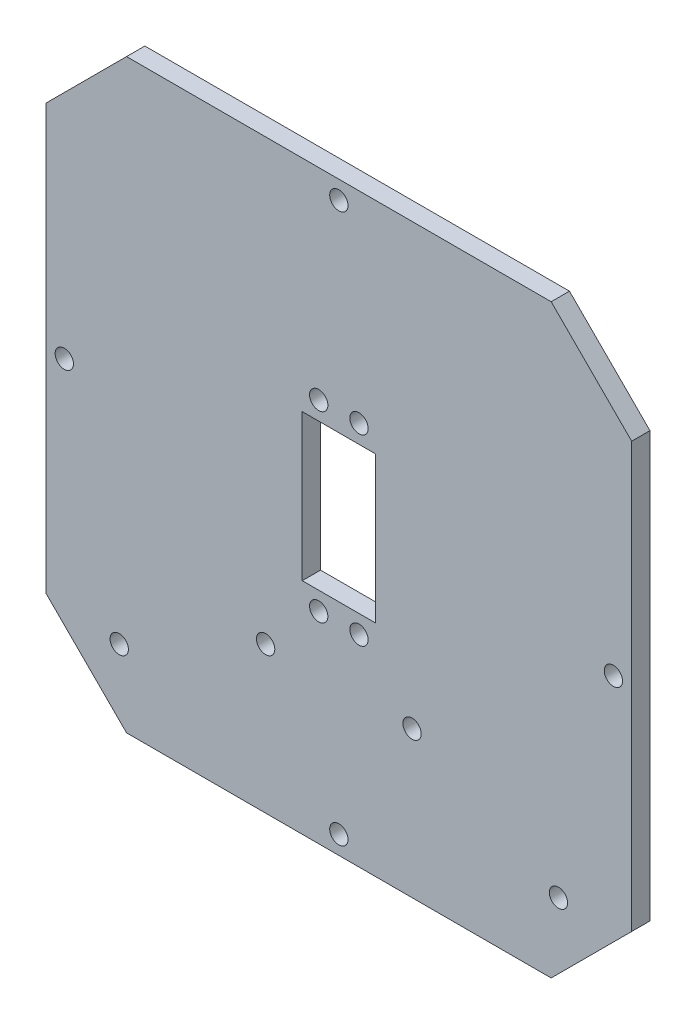
SolidWorks part; units mm, degrees
ref_plane "Plan de face" through (0, 0, 0) normal (0, 0, 1) x (1, 0, 0)
ref_plane "Plan de dessus" through (0, 0, 0) normal (0, 1, 0) x (1, 0, 0)
ref_plane "Plan de droite" through (0, 0, 0) normal (1, 0, 0) x (0, 0, -1)
sketch "Esquisse1" plane through (0, 0, 0) normal (0, 0, 1) x (1, 0, 0)
  line L1 (-28.3501, 34.1568) -> (131.6499, 34.1568)
  line L2 (-28.3501, 34.1568) -> (-28.3501, -125.8432)
  line L3 (-28.3501, -125.8432) -> (131.6499, -125.8432)
  line L4 (131.6499, 34.1568) -> (131.6499, -125.8432)
  dimension "D1" = 160
  dimension "D2" = 160
extrude "Boss.-Extru.1" add sketch "Esquisse1" along normal blind 5
chamfer "Chanfrein1" distance 22 angle 45 4 edges at (-28.3501, -125.8432, 2.5) (131.6499, -125.8432, 2.5) (131.6499, 34.1568, 2.5) (-28.3501, 34.1568, 2.5)
sketch "Esquisse2" plane through (0, 0, 5) normal (0, 0, 1) x (1, 0, 0)
  line L0 (131.6499, -103.8432) -> (131.6499, 12.1568) construction
  line L1 (41.6499, -25.8432) -> (61.6499, -25.8432)
  line L2 (41.6499, -25.8432) -> (41.6499, -65.8432)
  line L3 (41.6499, -65.8432) -> (61.6499, -65.8432)
  line L4 (61.6499, -25.8432) -> (61.6499, -65.8432)
  line L5 (109.6499, 34.1568) -> (-6.3501, 34.1568) construction
  dimension "D1" = 20
  dimension "D2" = 40
  dimension "D3" = 70
  dimension "D4" = 60
extrude "Enlèv. mat.-Extru.1" cut sketch "Esquisse2" against normal blind 5
sketch "Esquisse3" plane through (0, 0, 5) normal (0, 0, 1) x (1, 0, 0)
  line L0 (61.6499, -25.8432) -> (41.6499, -25.8432) construction
  line L1 (41.6499, -25.8432) -> (41.6499, -65.8432) construction
  line L2 (61.6499, -65.8432) -> (61.6499, -25.8432) construction
  line L3 (61.6499, -25.8432) -> (41.6499, -25.8432) construction
  circle A0 centre (46.1499, -20.8432) radius 2.5
  circle A1 centre (57.1499, -20.8432) radius 2.5
  dimension "D2" = 5
  dimension "D4" = 5
  dimension "D1" = 5
  dimension "D3" = 4.5
  dimension "D5" = 4.5
  dimension "D6" = 5
extrude "Enlèv. mat.-Extru.2" cut sketch "Esquisse3" against normal blind 5
sketch "Esquisse4" plane through (0, 0, 5) normal (0, 0, 1) x (1, 0, 0)
  line L0 (41.6499, -25.8432) -> (41.6499, -65.8432) construction
  line L2 (41.6499, -65.8432) -> (61.6499, -65.8432) construction
  line L3 (61.6499, -65.8432) -> (61.6499, -25.8432) construction
  circle A0 centre (46.1499, -70.8432) radius 2.5
  circle A1 centre (57.1499, -61.8432) radius 2.5
  dimension "D1" = 5
  dimension "D4" = 5
  dimension "D2" = 4.5
  dimension "D3" = 5
  dimension "D5" = 4.5
extrude "Enlèv. mat.-Extru.3" cut sketch "Esquisse4" against normal blind 5
sketch "Esquisse5" plane through (0, 0, 0) normal (0, 0, -1) x (-1, 0, 0)
  line L0 (-41.6499, -65.8432) -> (-61.6499, -65.8432) construction
  line L1 (-61.6499, -65.8432) -> (-61.6499, -25.8432) construction
  circle A0 centre (-57.1499, -70.8432) radius 2.5
  dimension "D1" = 5
  dimension "D2" = 5
  dimension "D3" = 4.5
extrude "Enlèv. mat.-Extru.4" cut sketch "Esquisse5" against normal blind 10
sketch "Esquisse6" plane through (0, 0, 5) normal (0, 0, 1) x (1, 0, 0)
  line L0 (109.6499, 34.1568) -> (-6.3501, 34.1568) construction
  line L1 (-28.3501, 12.1568) -> (-28.3501, -103.8432) construction
  circle A0 centre (51.6499, 29.1568) radius 2.5
  dimension "D1" = 5
  dimension "D2" = 5
  dimension "D3" = 80
extrude "Enlèv. mat.-Extru.5" cut sketch "Esquisse6" against normal blind 10
sketch "Esquisse7" plane through (0, 0, 5) normal (0, 0, 1) x (1, 0, 0)
  line L0 (-28.3501, 12.1568) -> (-28.3501, -103.8432) construction
  line L1 (-6.3501, -125.8432) -> (109.6499, -125.8432) construction
  circle A0 centre (-23.3501, -45.8432) radius 2.5
  dimension "D2" = 5
  dimension "D1" = 5
  dimension "D3" = 80
extrude "Enlèv. mat.-Extru.6" cut sketch "Esquisse7" against normal blind 10
sketch "Esquisse8" plane through (0, 0, 5) normal (0, 0, 1) x (1, 0, 0)
  line L0 (-6.3501, -125.8432) -> (109.6499, -125.8432) construction
  line L1 (131.6499, -103.8432) -> (131.6499, 12.1568) construction
  circle A0 centre (51.6499, -120.8432) radius 2.5
  circle A1 centre (126.6499, -45.8432) radius 2.5
  dimension "D3" = 5
  dimension "D4" = 5
  dimension "D1" = 5
  dimension "D2" = 5
  dimension "D5" = 80
  dimension "D6" = 80
extrude "Enlèv. mat.-Extru.7" cut sketch "Esquisse8" against normal blind 10
sketch "Esquisse9" plane through (0, 0, 5) normal (0, 0, 1) x (1, 0, 0)
  line L0 (131.6499, -103.8432) -> (131.6499, 12.1568) construction
  line L1 (-6.3501, -125.8432) -> (109.6499, -125.8432) construction
  line L2 (-28.3501, 12.1568) -> (-28.3501, -103.8432) construction
  circle A0 centre (111.6499, -105.8432) radius 2.5
  circle A1 centre (-8.3501, -105.8432) radius 2.5
  dimension "D2" = 5
  dimension "D6" = 5
  dimension "D1" = 20
  dimension "D3" = 20
  dimension "D4" = 20
  dimension "D5" = 20
extrude "Enlèv. mat.-Extru.8" cut sketch "Esquisse9" against normal blind 30
sketch "Esquisse10" plane through (0, 0, 0) normal (0, 0, -1) x (-1, 0, 0)
  line L0 (-131.6499, -103.8432) -> (-131.6499, 12.1568) construction
  line L1 (6.3501, -125.8432) -> (-109.6499, -125.8432) construction
  line L2 (28.3501, 12.1568) -> (28.3501, -103.8432) construction
  circle A0 centre (-71.6499, -85.8432) radius 2.5
  circle A1 centre (-31.6499, -85.8432) radius 2.5
  point P10 (-40.0114, -87.1714)
  dimension "D3" = 5
  dimension "D6" = 5
  dimension "D1" = 60
  dimension "D2" = 40
  dimension "D4" = 40
  dimension "D5" = 60
extrude "Enlèv. mat.-Extru.9" cut sketch "Esquisse10" against normal blind 30
